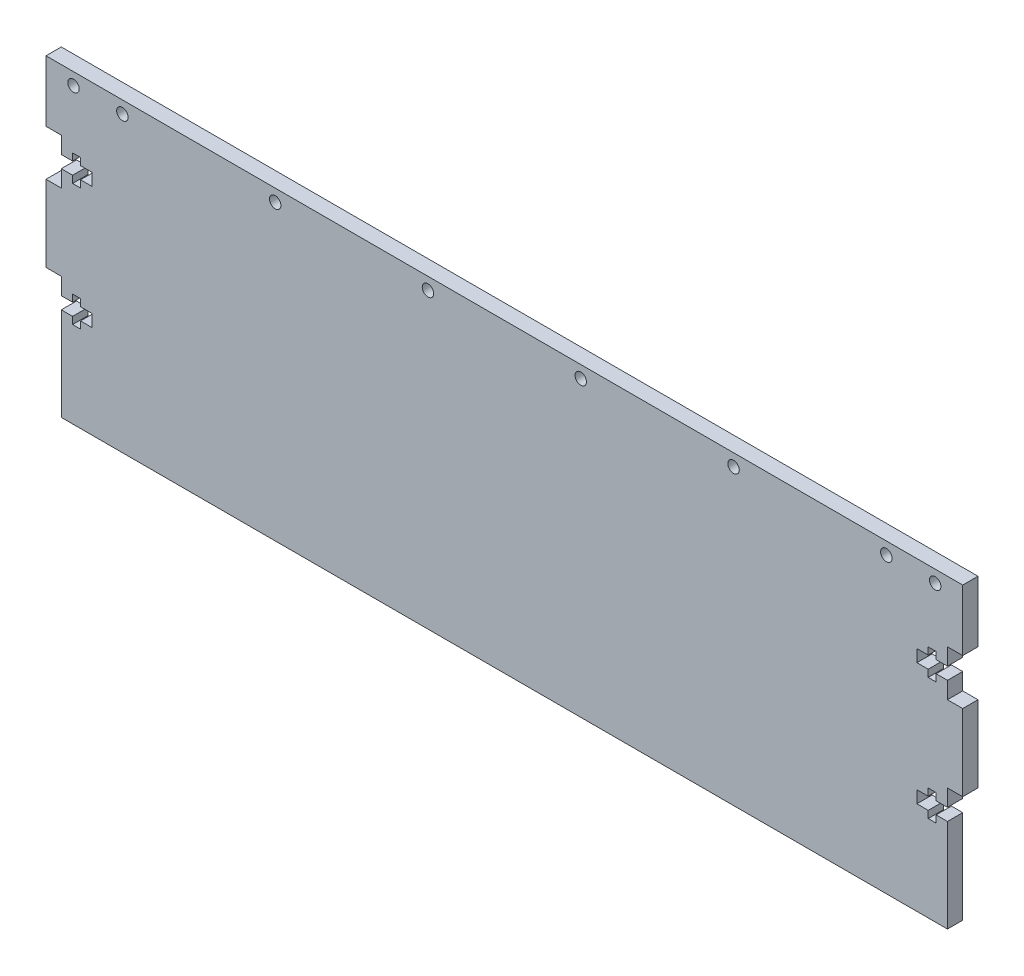
SolidWorks part; units mm, degrees
ref_plane "Front Plane" through (0, 0, 0) normal (0, 0, 1) x (1, 0, 0)
ref_plane "Top Plane" through (0, 0, 0) normal (0, 1, 0) x (1, 0, 0)
ref_plane "Right Plane" through (0, 0, 0) normal (1, 0, 0) x (0, 0, -1)
sketch "Sketch2" plane through (0, 0, 0) normal (0, 0, 1) x (1, 0, 0)
  line L1 (0, 0) -> (381, 0)
  line L2 (0, 0) -> (0, 127)
  line L3 (0, 127) -> (381, 127)
  line L4 (381, 0) -> (381, 127)
  dimension "D1" = 381
  dimension "D2" = 127
extrude "Boss-Extrude1" add sketch "Sketch2" along normal blind 6.35
sketch "Sketch5" plane through (0, 0, 0) normal (0, 0, -1) x (-1, 0, 0)
  line L1 (-381, 101.6) -> (-381, 82.55)
  line L2 (-381, 101.6) -> (-374.65, 101.6)
  line L3 (-374.65, 101.6) -> (-374.65, 94.615)
  line L4 (-381, 82.55) -> (-374.65, 82.55)
  line L6 (-374.65, 94.615) -> (-369.951, 94.615)
  line L7 (-361.95, 94.615) -> (-361.95, 89.535)
  line L8 (-374.65, 89.535) -> (-369.951, 89.535)
  line L9 (-366.649, 94.615) -> (-361.95, 94.615)
  line L10 (-366.649, 97.5741) -> (-366.649, 94.615)
  line L11 (-366.649, 97.5741) -> (-369.951, 97.5741)
  line L12 (-369.951, 97.5741) -> (-369.951, 94.615)
  line L13 (-366.649, 86.5759) -> (-369.951, 86.5759)
  line L14 (-366.649, 89.535) -> (-366.649, 86.5759)
  line L15 (-366.649, 89.535) -> (-361.95, 89.535)
  line L16 (-369.951, 89.535) -> (-369.951, 86.5759)
  line L17 (-374.65, 89.535) -> (-374.65, 82.55)
  line L18 (-381, 0) -> (-381, 127) construction
  line L19 (-381, 127) -> (0, 127) construction
  point P8 (-361.95, 92.075)
  dimension "D1" = 6.35
  dimension "D2" = 5.08
  dimension "D3" = 10.9982
  dimension "D4" = 3.302
  dimension "D5" = 19.05
  dimension "D6" = 25.4
  dimension "D7" = 19.05
extrude "Cut-Extrude3" cut sketch "Sketch5" against normal through all
pattern_linear "LPattern1" count 2 spacing 50.8 along (0, -1, 0) of "Cut-Extrude3"
ref_plane "Plane1" through (190.5, 0, 0) normal (-1, 0, 0) x (0, 0, 1)
mirror "Mirror1" about plane through (190.5, 0, 0) normal (-1, 0, 0) of "LPattern1", "Cut-Extrude3"
sketch "Sketch6" plane through (0, 0, 0) normal (0, 0, -1) x (-1, 0, 0)
  line L0 (-381, 127) -> (0, 127) construction
  line L1 (-381, 101.6) -> (-381, 127) construction
  circle A0 centre (-349.25, 121.92) radius 2.3813
  dimension "D1" = 4.7625
  dimension "D2" = 5.08
  dimension "D3" = 31.75
extrude "Cut-Extrude4" cut sketch "Sketch6" against normal through all
pattern_linear "LPattern2" count 6 spacing 63.5 along (-1, 0, 0) of "Cut-Extrude4"
sketch "Sketch7" plane through (0, 0, 0) normal (0, 0, -1) x (-1, 0, 0)
  line L0 (-381, 127) -> (0, 127) construction
  line L1 (-381, 101.6) -> (-381, 127) construction
  circle A0 centre (-369.57, 121.92) radius 2.3813
  dimension "D1" = 4.7625
  dimension "D2" = 5.08
  dimension "D3" = 11.43
extrude "Cut-Extrude5" cut sketch "Sketch7" against normal through all
mirror "Mirror2" about plane through (190.5, 0, 0) normal (-1, 0, 0) of "Cut-Extrude5"
sketch "Sketch8" plane through (0, 0, 0) normal (0, 0, -1) x (-1, 0, 0)
  line L0 (0, 0) -> (-381, 0) construction
  line L1 (-381, 31.75) -> (-374.65, 31.75)
  line L2 (-381, 31.75) -> (-381, 0)
  line L3 (-381, 0) -> (-374.65, 0)
  line L4 (-374.65, 31.75) -> (-374.65, 0)
  dimension "D1" = 6.35
extrude "Cut-Extrude6" cut sketch "Sketch8" against normal through all
mirror "Mirror3" about plane through (190.5, 0, 0) normal (-1, 0, 0) of "Cut-Extrude6"
